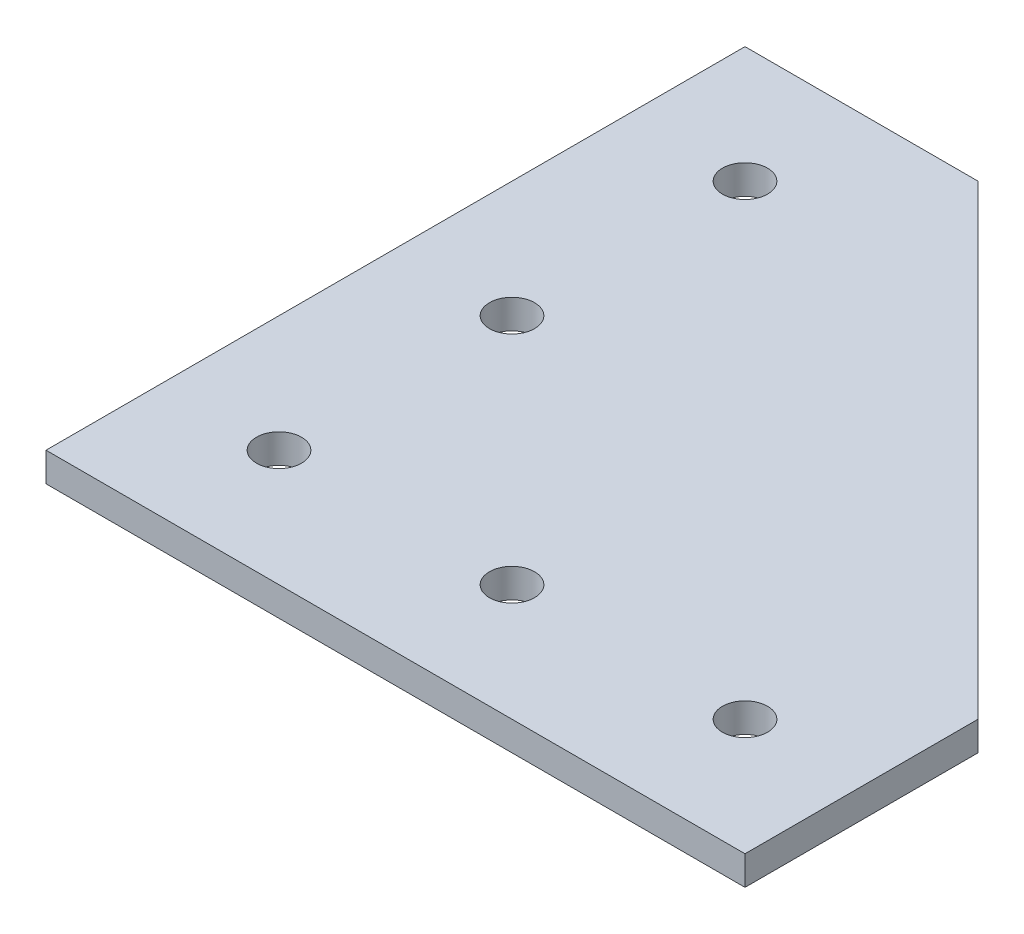
SolidWorks part; units mm, degrees
material "6061 Alloy"
ref_plane "Front Plane" through (0, 0, 0) normal (0, 0, 1) x (1, 0, 0)
ref_plane "Top Plane" through (0, 0, 0) normal (0, 1, 0) x (1, 0, 0)
ref_plane "Right Plane" through (0, 0, 0) normal (1, 0, 0) x (0, 0, -1)
sketch "Sketch1" plane through (0, 0, 0) normal (0, 1, 0) x (1, 0, 0)
  line L0 (0, 0) -> (0, 76.2)
  line L1 (0, 76.2) -> (25.4, 76.2)
  line L2 (76.2, 0) -> (76.2, 25.4)
  line L3 (76.2, 25.4) -> (25.4, 76.2)
  line L4 (76.2, 0) -> (0, 0)
  dimension "D1" = 76.2
  dimension "D2" = 76.2
  dimension "D3" = 25.4
  dimension "D4" = 25.4
extrude "Boss-Extrude1" add sketch "Sketch1" along normal blind 3.175
hole_wizard "#10 (0.1935) Diameter Hole1" positions "Sketch3" profile "Sketch2" hole size "#10" standard "ANSI Inch"
sketch "Sketch3" plane through (0, 0, 0) normal (0, -1, 0) x (-1, 0, 0)
  line L0 (0, 0) -> (-76.2, 0) construction
  line L1 (0, 76.2) -> (0, 0) construction
  line L6 (-25.4, 76.2) -> (0, 76.2) construction
  line L7 (-76.2, 0) -> (-76.2, 25.4) construction
  line L8 (-12.7, 12.7) -> (-63.5, 12.7) construction
  line L10 (-12.7, 12.7) -> (-12.7, 63.5) construction
  point P0 (-12.7, 12.7)
  point P2 (-12.7, 38.1)
  point P4 (-12.7, 63.5)
  point P6 (-38.1, 12.7)
  point P8 (-63.5, 12.7)
  point P47 (-12.7, 38.1)
  point P49 (-38.1, 12.7)
  dimension "D1" = 12.7
  dimension "D2" = 12.7
  dimension "D3" = 12.7
  dimension "D4" = 12.7
sketch "Sketch2" plane through (12.7, 0, -12.7) normal (1, 0, 0) x (0, 0, -1)
  line L0 (0, 0) -> (0, 26.8766)
  line L1 (0, 26.8766) -> (2.4574, 25.4)
  line L2 (2.4574, 25.4) -> (2.4574, 0)
  line L5 (2.4574, 0) -> (0, 0)
  line L10 (0, 26.8766) -> (-2.4575, 25.4) construction
  line L11 (0, -6.35) -> (0, 107.95) construction
  dimension "Hole Dia." = 4.9149
  dimension "Hole Depth" = 25.4
  dimension "Drill Angle" = 118
